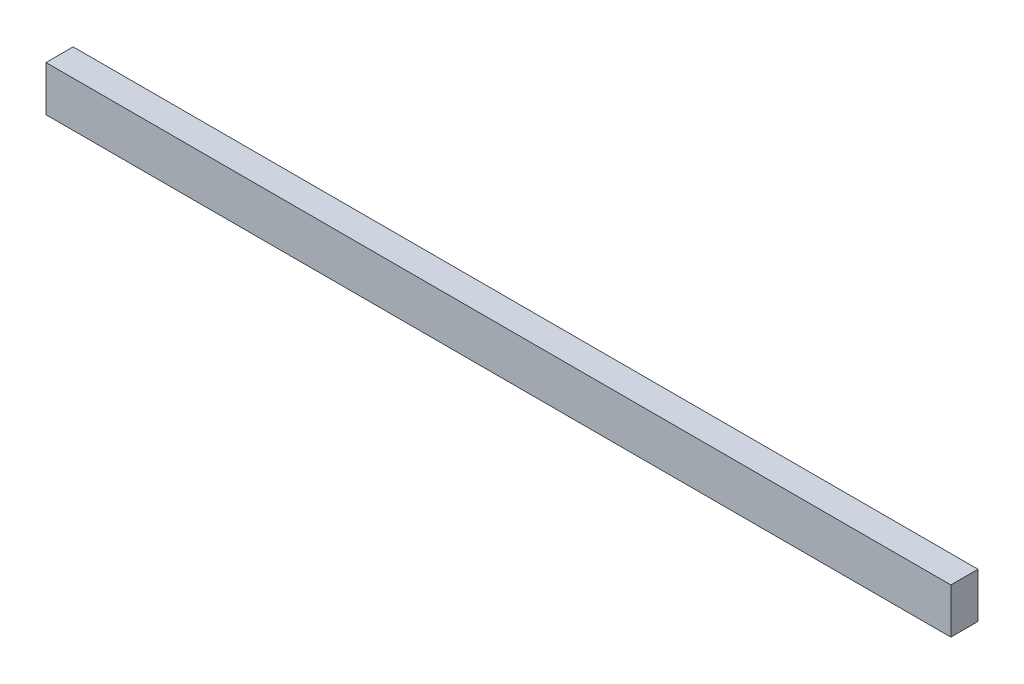
SolidWorks part; units mm, degrees
ref_plane "Front Plane" through (0, 0, 0) normal (0, 0, 1) x (1, 0, 0)
ref_plane "Top Plane" through (0, 0, 0) normal (0, 1, 0) x (1, 0, 0)
ref_plane "Right Plane" through (0, 0, 0) normal (1, 0, 0) x (0, 0, -1)
sketch "Sketch1" plane through (0, 0, 0) normal (0, 0, 1) x (1, 0, 0)
  line L1 (0, 0) -> (200, 0)
  line L2 (0, 0) -> (0, 10)
  line L3 (0, 10) -> (200, 10)
  line L4 (200, 0) -> (200, 10)
  dimension "D1" = 10
  dimension "D2" = 200
extrude "Boss-Extrude1" add sketch "Sketch1" along normal blind 6
